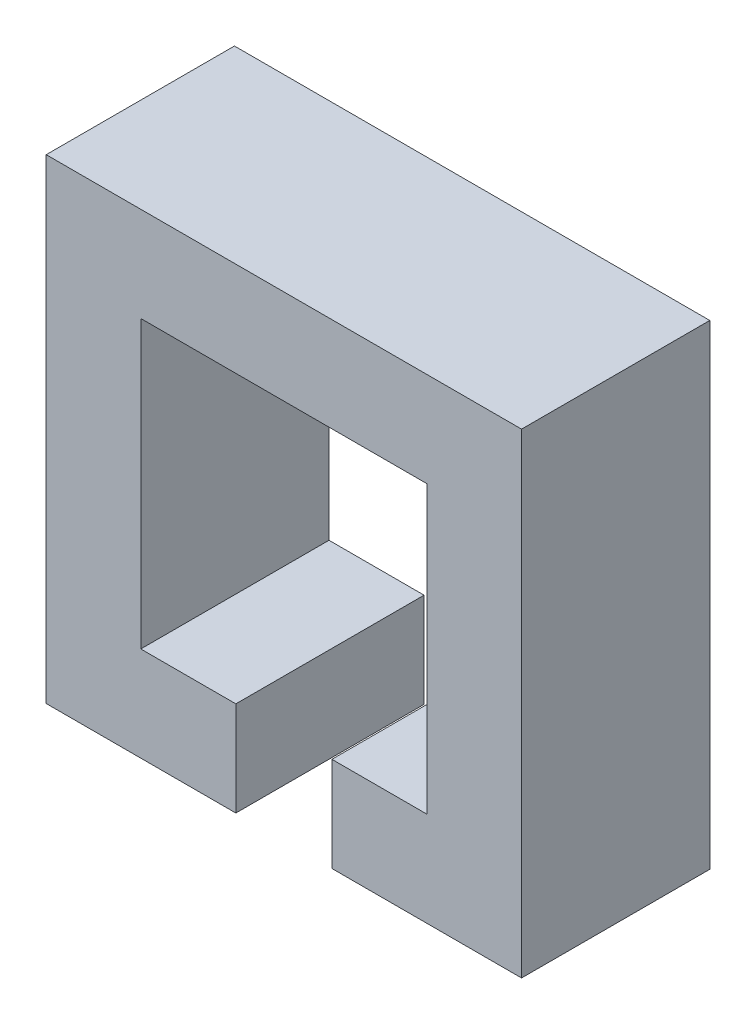
SolidWorks part; units mm, degrees
ref_plane "Front Plane" through (0, 0, 0) normal (0, 0, 1) x (1, 0, 0)
ref_plane "Top Plane" through (0, 0, 0) normal (0, 1, 0) x (1, 0, 0)
ref_plane "Right Plane" through (0, 0, 0) normal (1, 0, 0) x (0, 0, -1)
ref_plane "Plane1" through (0, 0, 9.9) normal (0, 0, 1) x (1, 0, 0)
sketch "Sketch1" plane through (0, 0, 9.9) normal (0, 0, 1) x (1, 0, 0)
  line L0 (-7.526, -25.026) -> (-7.526, -9.974)
  line L1 (-7.526, -9.974) -> (7.5265, -9.974)
  line L2 (7.5265, -9.974) -> (7.5265, -25.026)
  line L3 (7.5265, -25.026) -> (2.5265, -25.026)
  line L4 (2.5265, -25.026) -> (2.5265, -30)
  line L5 (2.5265, -30) -> (12.5, -30)
  line L6 (12.5, -30) -> (12.5, -5)
  line L7 (12.5, -5) -> (-12.5, -5)
  line L8 (-12.5, -5) -> (-12.5, -30)
  line L9 (-12.5, -30) -> (-2.526, -30)
  line L10 (-2.526, -30) -> (-2.526, -25.026)
  line L11 (-2.526, -25.026) -> (-7.526, -25.026)
  dimension "D1" = 25
extrude "Boss-Extrude1" add sketch "Sketch1" against normal blind 9.9
